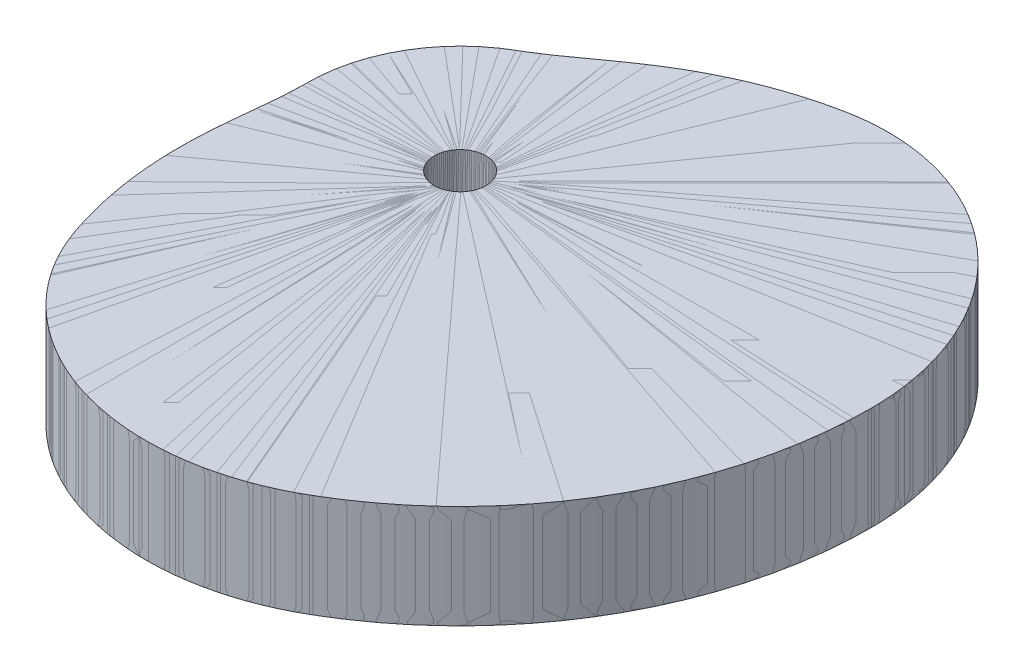
SolidWorks part; units mm, degrees
ref_plane "前视基准面" through (0, 0, 0) normal (0, 0, 1) x (1, 0, 0)
ref_plane "上视基准面" through (0, 0, 0) normal (0, 1, 0) x (1, 0, 0)
ref_plane "右视基准面" through (0, 0, 0) normal (1, 0, 0) x (0, 0, -1)
other "Configuration Table"
sketch "草图1" plane through (0, 0, 0) normal (0, 0, 1) x (1, 0, 0)
  line L0 (0, -20200) -> (0, 200) construction
  line L1 (5, 0) -> (80, 0)
  line L2 (80, 0) -> (80, -20)
  line L3 (80, -20) -> (5, -20)
  line L4 (5, -20) -> (5, 0)
revolve "旋转1" add sketch "草图1" angle 360 about L0
sketch "草图2" plane through (0, 0, 0) normal (0, 1, 0) x (1, 0, 0)
  line L0 (0, 0) -> (80, 0) construction
  arc A0 (79.5, 0) -> (79.027, 6.889) centre (29.0158, -0.0054) ccw
  arc A1 (79.027, 6.889) -> (77.6192, 13.6356) centre (29.3188, 0.0363) ccw
  arc A2 (77.6192, 13.6356) -> (75.3065, 20.1004) centre (29.7814, 0.1687) ccw
  arc A3 (75.3065, 20.1004) -> (72.1392, 26.149) centre (30.4291, 0.4546) ccw
  arc A4 (72.1392, 26.149) -> (68.1863, 31.6554) centre (31.21, 0.9379) ccw
  arc A5 (68.1863, 31.6554) -> (63.5342, 36.5035) centre (32.0595, 1.6461) ccw
  arc A6 (63.5342, 36.5035) -> (58.286, 40.5905) centre (32.9058, 2.5861) ccw
  arc A7 (58.286, 40.5905) -> (52.559, 43.8282) centre (33.6758, 3.7418) ccw
  arc A8 (52.559, 43.8282) -> (46.4828, 46.1451) centre (34.3014, 5.073) ccw
  arc A9 (46.4828, 46.1451) -> (40.1976, 47.4881) centre (34.7286, 6.5165) ccw
  arc A10 (40.1976, 47.4881) -> (33.8508, 47.8241) centre (34.9248, 7.9896) ccw
  arc A11 (33.8508, 47.8241) -> (27.59, 47.1393) centre (34.8892, 9.3651) ccw
  arc A12 (27.59, 47.1393) -> (21.6911, 45.7463) centre (41.7163, -25.8693) ccw
  arc A13 (21.6911, 45.7463) -> (16.3696, 44.035) centre (41.2849, -24.3103) ccw
  arc A14 (16.3696, 44.035) -> (11.6082, 42.1045) centre (41.16, -23.9463) ccw
  arc A15 (11.6082, 42.1045) -> (7.3715, 40.0439) centre (41.8148, -25.3862) ccw
  arc A16 (7.3715, 40.0439) -> (3.6125, 37.9311) centre (44.1291, -29.7547) ccw
  arc A17 (3.6125, 37.9311) -> (0.2748, 35.8322) centre (50.161, -39.7958) ccw
  arc A18 (0.2748, 35.8322) -> (-2.7058, 33.8002) centre (66.4018, -64.3674) ccw
  arc A19 (-2.7058, 33.8002) -> (-5.3989, 31.8746) centre (130.8056, -155.763) ccw
  arc A20 (-5.3989, 31.8746) -> (-7.8774, 30.0809) centre (-573.3815, 814.0785) cw
  arc A21 (-7.8774, 30.0809) -> (-10.2149, 28.4313) centre (-88.8574, 142.3512) cw
  arc A22 (-10.2149, 28.4313) -> (-12.4833, 26.9248) centre (-53.86, 91.691) cw
  arc A23 (-12.4833, 26.9248) -> (-14.75, 25.5477) centre (-44.8377, 77.6266) cw
  arc A24 (-14.75, 25.5477) -> (-29.5, 0) centre (0, 0) ccw
  arc A25 (-29.5, 0) -> (-29.5592, -2.6515) centre (-89.6454, 0.0173) cw
  arc A26 (-29.5592, -2.6515) -> (-29.7297, -5.3693) centre (-106.3368, 0.7987) cw
  arc A27 (-29.7297, -5.3693) -> (-29.9895, -8.2184) centre (-167.7085, 5.7772) cw
  arc A28 (-29.9895, -8.2184) -> (-30.3036, -11.2617) centre (-991.7034, 89.5237) cw
  arc A29 (-30.3036, -11.2617) -> (-30.6248, -14.5568) centre (200.2976, -35.3995) ccw
  arc A30 (-30.6248, -14.5568) -> (-30.8942, -18.1541) centre (88.9447, -25.3219) ccw
  arc A31 (-30.8942, -18.1541) -> (-31.0431, -22.0941) centre (59.5447, -23.5428) ccw
  arc A32 (-31.0431, -22.0941) -> (-30.9933, -26.4058) centre (47.8328, -23.3396) ccw
  arc A33 (-30.9933, -26.4058) -> (-30.6595, -31.1053) centre (42.8925, -23.5195) ccw
  arc A34 (-30.6595, -31.1053) -> (-29.9506, -36.194) centre (41.3181, -23.6724) ccw
  arc A35 (-29.9506, -36.194) -> (-28.772, -41.6582) centre (41.6958, -23.5986) ccw
  arc A36 (-28.772, -41.6582) -> (-27.0288, -47.4633) centre (43.2617, -23.1927) ccw
  arc A37 (-27.0288, -47.4633) -> (-24.4914, -53.2277) centre (9.3342, -34.8975) ccw
  arc A38 (-24.4914, -53.2277) -> (-21.0271, -58.5562) centre (10.5432, -34.2405) ccw
  arc A39 (-21.0271, -58.5562) -> (-16.7214, -63.3279) centre (11.7208, -33.3341) ccw
  arc A40 (-16.7214, -63.3279) -> (-11.6768, -67.4315) centre (12.7573, -32.2424) ccw
  arc A41 (-11.6768, -67.4315) -> (-6.0094, -70.7724) centre (13.5974, -31.035) ccw
  arc A42 (-6.0094, -70.7724) -> (0.1541, -73.274) centre (14.2133, -29.7903) ccw
  arc A43 (0.1541, -73.274) -> (6.6788, -74.8787) centre (14.6042, -28.5873) ccw
  arc A44 (6.6788, -74.8787) -> (13.4239, -75.5489) centre (14.7927, -27.4976) ccw
  arc A45 (13.4239, -75.5489) -> (20.2458, -75.2676) centre (14.8209, -26.5797) ccw
  arc A46 (20.2458, -75.2676) -> (27.0008, -74.038) centre (14.7446, -25.8758) ccw
  arc A47 (27.0008, -74.038) -> (33.5475, -71.8839) centre (14.6279, -25.409) ccw
  arc A48 (33.5475, -71.8839) -> (39.75, -68.849) centre (14.5126, -25.1257) ccw
  arc A49 (39.75, -68.849) -> (79.5, 0) centre (0, 0) ccw
extrude "切除-拉伸1" cut sketch "草图2" along normal blind 10 and the other way blind 30 flip side to cut
sketch "草图3" plane through (0, 0, 0) normal (0, 1, 0) x (1, 0, 0)
  circle A0 centre (0, 0) radius 5 construction
  circle A1 centre (0, 0) radius 5
  arc A50 (33.5475, -71.8839) -> (39.75, -68.849) centre (14.5126, -25.1257) ccw
  arc A51 (39.75, -68.849) -> (79.5, 0) centre (0, 0) ccw
  arc A52 (79.5, 0) -> (79.027, 6.889) centre (29.0158, -0.0054) ccw
  arc A53 (79.027, 6.889) -> (77.6192, 13.6356) centre (29.3188, 0.0363) ccw
  arc A54 (77.6192, 13.6356) -> (75.3065, 20.1004) centre (29.7814, 0.1687) ccw
  arc A55 (75.3065, 20.1004) -> (72.1392, 26.149) centre (30.4291, 0.4546) ccw
  arc A56 (72.1392, 26.149) -> (68.1863, 31.6554) centre (31.21, 0.9379) ccw
  arc A57 (68.1863, 31.6554) -> (63.5342, 36.5035) centre (32.0595, 1.6461) ccw
  arc A58 (63.5342, 36.5035) -> (58.286, 40.5905) centre (32.9058, 2.5861) ccw
  arc A59 (58.286, 40.5905) -> (52.559, 43.8282) centre (33.6758, 3.7418) ccw
  arc A60 (52.559, 43.8282) -> (46.4828, 46.1451) centre (34.3014, 5.073) ccw
  arc A61 (46.4828, 46.1451) -> (40.1976, 47.4881) centre (34.7286, 6.5165) ccw
  arc A62 (40.1976, 47.4881) -> (33.8508, 47.8241) centre (34.9248, 7.9896) ccw
  arc A63 (33.8508, 47.8241) -> (27.59, 47.1393) centre (34.8892, 9.3651) ccw
  arc A64 (27.59, 47.1393) -> (21.6911, 45.7463) centre (41.7163, -25.8693) ccw
  arc A65 (21.6911, 45.7463) -> (16.3696, 44.035) centre (41.2849, -24.3103) ccw
  arc A66 (16.3696, 44.035) -> (11.6082, 42.1045) centre (41.16, -23.9463) ccw
  arc A67 (11.6082, 42.1045) -> (7.3715, 40.0439) centre (41.8148, -25.3862) ccw
  arc A68 (7.3715, 40.0439) -> (3.6125, 37.9311) centre (44.1291, -29.7547) ccw
  arc A69 (3.6125, 37.9311) -> (0.2748, 35.8322) centre (50.161, -39.7958) ccw
  arc A70 (0.2748, 35.8322) -> (-2.7058, 33.8002) centre (66.4018, -64.3674) ccw
  arc A71 (-2.7058, 33.8002) -> (-5.3989, 31.8746) centre (130.8056, -155.763) ccw
  arc A72 (-7.8774, 30.0809) -> (-5.3989, 31.8746) centre (-573.3815, 814.0785) ccw
  arc A73 (-10.2149, 28.4313) -> (-7.8774, 30.0809) centre (-88.8574, 142.3512) ccw
  arc A74 (-12.4833, 26.9248) -> (-10.2149, 28.4313) centre (-53.86, 91.691) ccw
  arc A75 (-14.75, 25.5477) -> (-12.4833, 26.9248) centre (-44.8377, 77.6266) ccw
  arc A76 (-14.75, 25.5477) -> (-29.5, 0) centre (0, 0) ccw
  arc A77 (-29.5592, -2.6515) -> (-29.5, 0) centre (-89.6454, 0.0173) ccw
  arc A78 (-29.7297, -5.3693) -> (-29.5592, -2.6515) centre (-106.3368, 0.7987) ccw
  arc A79 (-29.9895, -8.2184) -> (-29.7297, -5.3693) centre (-167.7085, 5.7772) ccw
  arc A80 (-30.3036, -11.2617) -> (-29.9895, -8.2184) centre (-991.7034, 89.5237) ccw
  arc A81 (-30.3036, -11.2617) -> (-30.6248, -14.5568) centre (200.2976, -35.3995) ccw
  arc A82 (-30.6248, -14.5568) -> (-30.8942, -18.1541) centre (88.9447, -25.3219) ccw
  arc A83 (-30.8942, -18.1541) -> (-31.0431, -22.0941) centre (59.5447, -23.5428) ccw
  arc A84 (-31.0431, -22.0941) -> (-30.9933, -26.4058) centre (47.8328, -23.3396) ccw
  arc A85 (-30.9933, -26.4058) -> (-30.6595, -31.1053) centre (42.8925, -23.5195) ccw
  arc A86 (-30.6595, -31.1053) -> (-29.9506, -36.194) centre (41.3181, -23.6724) ccw
  arc A87 (-29.9506, -36.194) -> (-28.772, -41.6582) centre (41.6958, -23.5986) ccw
  arc A88 (-28.772, -41.6582) -> (-27.0288, -47.4633) centre (43.2617, -23.1927) ccw
  arc A89 (-27.0288, -47.4633) -> (-24.4914, -53.2277) centre (9.3342, -34.8975) ccw
  arc A90 (-24.4914, -53.2277) -> (-21.0271, -58.5562) centre (10.5432, -34.2405) ccw
  arc A91 (-21.0271, -58.5562) -> (-16.7214, -63.3279) centre (11.7208, -33.3341) ccw
  arc A92 (-16.7214, -63.3279) -> (-11.6768, -67.4315) centre (12.7573, -32.2424) ccw
  arc A93 (-11.6768, -67.4315) -> (-6.0094, -70.7724) centre (13.5974, -31.035) ccw
  arc A94 (-6.0094, -70.7724) -> (0.1541, -73.274) centre (14.2133, -29.7903) ccw
  arc A95 (0.1541, -73.274) -> (6.6788, -74.8787) centre (14.6042, -28.5873) ccw
  arc A96 (6.6788, -74.8787) -> (13.4239, -75.5489) centre (14.7927, -27.4976) ccw
  arc A97 (13.4239, -75.5489) -> (20.2458, -75.2676) centre (14.8209, -26.5797) ccw
  arc A98 (20.2458, -75.2676) -> (27.0008, -74.038) centre (14.7446, -25.8758) ccw
  arc A99 (27.0008, -74.038) -> (33.5475, -71.8839) centre (14.6279, -25.409) ccw
  arc A100 (33.5475, -71.8839) -> (39.75, -68.849) centre (14.5126, -25.1257) ccw construction
  arc A101 (39.75, -68.849) -> (79.5, 0) centre (0, 0) ccw construction
  arc A102 (79.5, 0) -> (79.027, 6.889) centre (29.0158, -0.0054) ccw construction
  arc A103 (79.027, 6.889) -> (77.6192, 13.6356) centre (29.3188, 0.0363) ccw construction
  arc A104 (77.6192, 13.6356) -> (75.3065, 20.1004) centre (29.7814, 0.1687) ccw construction
  arc A105 (75.3065, 20.1004) -> (72.1392, 26.149) centre (30.4291, 0.4546) ccw construction
  arc A106 (72.1392, 26.149) -> (68.1863, 31.6554) centre (31.21, 0.9379) ccw construction
  arc A107 (68.1863, 31.6554) -> (63.5342, 36.5035) centre (32.0595, 1.6461) ccw construction
  arc A108 (63.5342, 36.5035) -> (58.286, 40.5905) centre (32.9058, 2.5861) ccw construction
  arc A109 (58.286, 40.5905) -> (52.559, 43.8282) centre (33.6758, 3.7418) ccw construction
  arc A110 (52.559, 43.8282) -> (46.4828, 46.1451) centre (34.3014, 5.073) ccw construction
  arc A111 (46.4828, 46.1451) -> (40.1976, 47.4881) centre (34.7286, 6.5165) ccw construction
  arc A112 (40.1976, 47.4881) -> (33.8508, 47.8241) centre (34.9248, 7.9896) ccw construction
  arc A113 (33.8508, 47.8241) -> (27.59, 47.1393) centre (34.8892, 9.3651) ccw construction
  arc A114 (27.59, 47.1393) -> (21.6911, 45.7463) centre (41.7163, -25.8693) ccw construction
  arc A115 (21.6911, 45.7463) -> (16.3696, 44.035) centre (41.2849, -24.3103) ccw construction
  arc A116 (16.3696, 44.035) -> (11.6082, 42.1045) centre (41.16, -23.9463) ccw construction
  arc A117 (11.6082, 42.1045) -> (7.3715, 40.0439) centre (41.8148, -25.3862) ccw construction
  arc A118 (7.3715, 40.0439) -> (3.6125, 37.9311) centre (44.1291, -29.7547) ccw construction
  arc A119 (3.6125, 37.9311) -> (0.2748, 35.8322) centre (50.161, -39.7958) ccw construction
  arc A120 (0.2748, 35.8322) -> (-2.7058, 33.8002) centre (66.4018, -64.3674) ccw construction
  arc A121 (-2.7058, 33.8002) -> (-5.3989, 31.8746) centre (130.8056, -155.763) ccw construction
  arc A122 (-7.8774, 30.0809) -> (-5.3989, 31.8746) centre (-573.3815, 814.0785) ccw construction
  arc A123 (-10.2149, 28.4313) -> (-7.8774, 30.0809) centre (-88.8574, 142.3512) ccw construction
  arc A124 (-12.4833, 26.9248) -> (-10.2149, 28.4313) centre (-53.86, 91.691) ccw construction
  arc A125 (-14.75, 25.5477) -> (-12.4833, 26.9248) centre (-44.8377, 77.6266) ccw construction
  arc A126 (-14.75, 25.5477) -> (-29.5, 0) centre (0, 0) ccw construction
  arc A127 (-29.5592, -2.6515) -> (-29.5, 0) centre (-89.6454, 0.0173) ccw construction
  arc A128 (-29.7297, -5.3693) -> (-29.5592, -2.6515) centre (-106.3368, 0.7987) ccw construction
  arc A129 (-29.9895, -8.2184) -> (-29.7297, -5.3693) centre (-167.7085, 5.7772) ccw construction
  arc A130 (-30.3036, -11.2617) -> (-29.9895, -8.2184) centre (-991.7034, 89.5237) ccw construction
  arc A131 (-30.3036, -11.2617) -> (-30.6248, -14.5568) centre (200.2976, -35.3995) ccw construction
  arc A132 (-30.6248, -14.5568) -> (-30.8942, -18.1541) centre (88.9447, -25.3219) ccw construction
  arc A133 (-30.8942, -18.1541) -> (-31.0431, -22.0941) centre (59.5447, -23.5428) ccw construction
  arc A134 (-31.0431, -22.0941) -> (-30.9933, -26.4058) centre (47.8328, -23.3396) ccw construction
  arc A135 (-30.9933, -26.4058) -> (-30.6595, -31.1053) centre (42.8925, -23.5195) ccw construction
  arc A136 (-30.6595, -31.1053) -> (-29.9506, -36.194) centre (41.3181, -23.6724) ccw construction
  arc A137 (-29.9506, -36.194) -> (-28.772, -41.6582) centre (41.6958, -23.5986) ccw construction
  arc A138 (-28.772, -41.6582) -> (-27.0288, -47.4633) centre (43.2617, -23.1927) ccw construction
  arc A139 (-27.0288, -47.4633) -> (-24.4914, -53.2277) centre (9.3342, -34.8975) ccw construction
  arc A140 (-24.4914, -53.2277) -> (-21.0271, -58.5562) centre (10.5432, -34.2405) ccw construction
  arc A141 (-21.0271, -58.5562) -> (-16.7214, -63.3279) centre (11.7208, -33.3341) ccw construction
  arc A142 (-16.7214, -63.3279) -> (-11.6768, -67.4315) centre (12.7573, -32.2424) ccw construction
  arc A143 (-11.6768, -67.4315) -> (-6.0094, -70.7724) centre (13.5974, -31.035) ccw construction
  arc A144 (-6.0094, -70.7724) -> (0.1541, -73.274) centre (14.2133, -29.7903) ccw construction
  arc A145 (0.1541, -73.274) -> (6.6788, -74.8787) centre (14.6042, -28.5873) ccw construction
  arc A146 (6.6788, -74.8787) -> (13.4239, -75.5489) centre (14.7927, -27.4976) ccw construction
  arc A147 (13.4239, -75.5489) -> (20.2458, -75.2676) centre (14.8209, -26.5797) ccw construction
  arc A148 (20.2458, -75.2676) -> (27.0008, -74.038) centre (14.7446, -25.8758) ccw construction
  arc A149 (27.0008, -74.038) -> (33.5475, -71.8839) centre (14.6279, -25.409) ccw construction
  spline S0 degree 3 poles (15.132, -75.5679) (16.2711, -75.5606) (17.4092, -75.5137) (18.5451, -75.4271) (18.7027, -75.4151) (19.0178, -75.3895) (19.4901, -75.3467) (19.8047, -75.315) (19.9619, -75.2984) (20.1833, -75.275) (20.6257, -75.2253) (21.2884, -75.1418) (21.7293, -75.0802) (21.9495, -75.0479) (23.0829, -74.8819) (24.2098, -74.6767) (25.329, -74.4328) (25.4687, -74.4023) (25.7479, -74.3402) (26.1659, -74.2434) (26.4439, -74.1765) (26.5828, -74.1424) (26.8153, -74.0854) (27.2796, -73.968) (27.9736, -73.7818) (28.4344, -73.6511) (28.6643, -73.5842) (29.7682, -73.2625) (30.8604, -72.9032) (31.9396, -72.5065) (32.2995, -72.3742) (33.0163, -72.1013) (34.0825, -71.6672) (34.7861, -71.3619) (35.1362, -71.2052) (36.1876, -70.7346) (37.2224, -70.2283) (38.2392, -69.6869) (38.4087, -69.5967) (38.7465, -69.4143) (39.2506, -69.1357) (39.5838, -68.945) (39.75, -68.849) (39.9167, -68.7528) (40.2494, -68.5591) (40.7464, -68.2649) (41.0763, -68.0663) (41.2408, -67.9665) (64.9876, -53.5574) (78.8759, -29.5022) (79.4811, -1.7324) (79.4853, -1.5399) (79.4923, -1.155) (79.4986, -0.5775) (79.5, -0.1925) (79.5, 0) (79.5, 0.192) (79.4986, 0.5759) (79.4878, 1.1517) (79.4768, 1.5355) (79.4703, 1.7273) (79.4307, 2.8786) (79.3518, 4.0279) (79.2336, 5.1738) (79.1943, 5.5553) (79.1069, 6.3173) (78.9497, 7.4577) (78.8276, 8.2149) (78.7622, 8.5928) (78.5662, 9.7257) (78.3313, 10.8513) (78.0579, 11.9681) (78.001, 12.2007) (77.8837, 12.665) (77.6979, 13.3591) (77.5675, 13.8199) (77.5006, 14.0498) (77.4607, 14.1872) (77.3796, 14.4614) (77.2545, 14.8718) (77.1687, 15.1446) (77.1252, 15.2808) (76.7769, 16.3721) (76.391, 17.4506) (75.9682, 18.5151) (75.886, 18.722) (75.7189, 19.1346) (75.4599, 19.7503) (75.2817, 20.1583) (75.1913, 20.3617) (75.127, 20.5061) (74.9972, 20.7944) (74.7982, 21.2249) (74.6627, 21.5105) (74.5943, 21.6531) (74.1014, 22.68) (73.573, 23.6891) (73.0097, 24.6792) (72.9042, 24.8646) (72.6909, 25.234) (72.3635, 25.784) (72.1406, 26.1478) (72.0279, 26.3289) (71.9408, 26.4689) (71.7652, 26.7482) (71.4973, 27.1643) (71.3159, 27.4398) (71.2245, 27.5771) (70.5978, 28.5184) (69.9383, 29.4371) (69.2468, 30.332) (69.1203, 30.4956) (68.8653, 30.8212) (68.4765, 31.3047) (68.2132, 31.6236) (68.0805, 31.7822) (67.9724, 31.9114) (67.7549, 32.1687) (67.4243, 32.551) (67.2013, 32.8035) (67.0891, 32.9291) (66.3424, 33.7652) (65.5662, 34.5741) (64.7616, 35.3547) (64.617, 35.495) (64.3261, 35.7736) (63.8843, 36.186) (63.5863, 36.457) (63.4364, 36.5916) (63.3097, 36.7054) (63.055, 36.9315) (62.6691, 37.2664) (62.4093, 37.4868) (62.2789, 37.5963) (61.4286, 38.3097) (60.5529, 38.9916) (59.653, 39.6412) (59.4937, 39.7562) (59.1736, 39.9841) (58.6889, 40.3199) (58.363, 40.5395) (58.1994, 40.6482) (58.0567, 40.7431) (57.7702, 40.9311) (57.3371, 41.2081) (57.0463, 41.3894) (56.9003, 41.4792) (55.9655, 42.0545) (55.0099, 42.5948) (54.0349, 43.0991) (53.8646, 43.1872) (53.523, 43.3611) (53.0071, 43.6154) (52.6611, 43.7804) (52.4876, 43.8617) (52.3318, 43.9348) (52.0194, 44.079) (51.5481, 44.2896) (51.2323, 44.4262) (51.074, 44.4936) (50.0755, 44.9184) (49.0616, 45.305) (48.0338, 45.6528) (47.8569, 45.7127) (47.5025, 45.8301) (46.9684, 45.9992) (46.611, 46.1073) (46.432, 46.1601) (46.2662, 46.209) (45.9342, 46.3049) (45.4342, 46.4422) (45.0998, 46.5297) (44.9323, 46.5723) (43.893, 46.8371) (42.8441, 47.0612) (41.7873, 47.2444) (41.6086, 47.2753) (41.2508, 47.3349) (40.7129, 47.4173) (40.3536, 47.4674) (40.1739, 47.4913) (40.0013, 47.5142) (39.6559, 47.5579) (39.1369, 47.6164) (38.7905, 47.651) (38.6172, 47.6671) (37.5611, 47.7654) (36.5019, 47.8214) (35.4413, 47.8352) (35.2646, 47.8375) (34.9111, 47.8397) (34.3809, 47.836) (34.0275, 47.8288) (33.8508, 47.8241) (33.6758, 47.8193) (33.3257, 47.8076) (32.8008, 47.7826) (32.4511, 47.7611) (32.2764, 47.7493) (31.2277, 47.6779) (30.1828, 47.5636) (29.1434, 47.4066) (28.9702, 47.3804) (28.6242, 47.3258) (28.1061, 47.2379) (27.762, 47.1726) (27.59, 47.1393) (27.4247, 47.1073) (27.0942, 47.0422) (26.5991, 46.9412) (26.2696, 46.8716) (26.1049, 46.8362) (25.1169, 46.6241) (24.1334, 46.3919) (23.1548, 46.1396) (22.9918, 46.0976) (22.6659, 46.0124) (22.1779, 45.8813) (21.8533, 45.7917) (21.6911, 45.7463) (21.5415, 45.7045) (21.2426, 45.6199) (20.7951, 45.4901) (20.4973, 45.4016) (20.3486, 45.3569) (19.4561, 45.0887) (18.5689, 44.8034) (17.6874, 44.5011) (17.5405, 44.4507) (17.247, 44.349) (16.8077, 44.1936) (16.5155, 44.0882) (16.3696, 44.035) (16.2355, 43.9861) (15.9675, 43.8875) (15.5665, 43.7372) (15.2998, 43.6354) (15.1666, 43.5842) (14.3672, 43.2765) (13.5735, 42.9547) (12.7855, 42.6188) (12.6542, 42.5628) (12.3919, 42.4501) (11.9994, 42.2787) (11.7385, 42.1629) (11.6082, 42.1045) (11.4888, 42.0511) (11.2501, 41.9435) (10.893, 41.7802) (10.6555, 41.6701) (10.5369, 41.6148) (9.8252, 41.2825) (9.1189, 40.939) (8.4182, 40.5843) (8.3014, 40.5252) (8.0682, 40.4063) (7.7192, 40.2263) (7.4873, 40.1049) (7.3715, 40.0439) (7.2655, 39.9881) (7.0538, 39.8759) (6.7369, 39.7063) (6.5262, 39.5923) (6.421, 39.535) (5.7896, 39.1914) (5.163, 38.8392) (4.5413, 38.4785) (4.4377, 38.4184) (4.2307, 38.2977) (3.9211, 38.1153) (3.7153, 37.9927) (3.6125, 37.9311) (3.5185, 37.8748) (3.3308, 37.7619) (3.0498, 37.5916) (2.8629, 37.4773) (2.7695, 37.42) (2.2094, 37.0763) (1.6531, 36.7264) (1.1006, 36.3705) (1.0085, 36.3112) (0.8245, 36.1923) (0.5492, 36.013) (0.3662, 35.8926) (0.2748, 35.8322) (0.1911, 35.777) (0.024, 35.6664) (-0.2263, 35.4999) (-0.3929, 35.3885) (-0.4761, 35.3326) (-0.9754, 34.9977) (-1.4722, 34.659) (-1.9664, 34.3166) (-2.0488, 34.2596) (-2.2134, 34.1452) (-2.46, 33.9732) (-2.6239, 33.8579) (-2.7058, 33.8002) (-2.781, 33.7473) (-2.9313, 33.6413) (-3.1566, 33.482) (-3.3067, 33.3757) (-3.3817, 33.3224) (-3.8317, 33.0031) (-4.2805, 32.6821) (-4.7282, 32.3596) (-4.8718, 32.2562) (-5.1587, 32.049) (-5.5883, 31.7371) (-5.8747, 31.5293) (-6.018, 31.4254) (-6.4308, 31.1261) (-6.8439, 30.8272) (-7.2572, 30.5286) (-7.3261, 30.4788) (-7.4639, 30.3793) (-7.6706, 30.23) (-7.8085, 30.1306) (-7.8774, 30.0809) (-7.9418, 30.0344) (-8.0708, 29.9414) (-8.2646, 29.8025) (-8.3939, 29.7101) (-8.4586, 29.6639) (-8.8467, 29.387) (-9.2363, 29.1121) (-9.6273, 28.8391) (-9.6925, 28.7936) (-9.8229, 28.7028) (-10.0188, 28.5668) (-10.1495, 28.4764) (-10.2149, 28.4313) (-10.2772, 28.3883) (-10.4017, 28.3025) (-10.5892, 28.1745) (-10.7143, 28.0895) (-10.777, 28.0471) (-11.1528, 27.7927) (-11.5309, 27.5416) (-11.9112, 27.2939) (-11.9746, 27.2526) (-12.1015, 27.1702) (-12.2922, 27.0472) (-12.4196, 26.9656) (-12.4833, 26.9248) (-12.5454, 26.8852) (-12.6697, 26.806) (-12.8568, 26.6883) (-12.9817, 26.6102) (-13.0443, 26.5712) (-13.4195, 26.3375) (-13.7973, 26.108) (-14.1777, 25.8826) (-14.3046, 25.8074) (-14.5591, 25.6579) (-14.9427, 25.4368) (-15.196, 25.2854) (-15.3221, 25.2088) (-24.1155, 19.8641) (-29.2606, 10.9525) (-29.4925, 0.6649) (-29.4958, 0.5174) (-29.5003, 0.2223) (-29.4999, -0.2204) (-29.5022, -0.5155) (-29.5038, -0.6631) (-29.5088, -1.1051) (-29.5187, -1.5471) (-29.5335, -1.9889) (-29.5359, -2.0626) (-29.5411, -2.2098) (-29.5495, -2.4307) (-29.5559, -2.5779) (-29.5592, -2.6515) (-29.5626, -2.7271) (-29.5696, -2.8782) (-29.5808, -3.1049) (-29.5887, -3.256) (-29.5928, -3.3315) (-29.6172, -3.7847) (-29.6456, -4.2377) (-29.678, -4.6904) (-29.6834, -4.7659) (-29.6945, -4.9168) (-29.7115, -5.1431) (-29.7236, -5.2939) (-29.7297, -5.3693) (-29.7361, -5.4485) (-29.749, -5.6069) (-29.7688, -5.8445) (-29.7823, -6.0029) (-29.7891, -6.0821) (-29.8299, -6.5571) (-29.8732, -7.032) (-29.919, -7.5066) (-29.9266, -7.5858) (-29.942, -7.7439) (-29.9654, -7.9812) (-29.9814, -8.1394) (-29.9895, -8.2184) (-29.9981, -8.303) (-30.0153, -8.4721) (-30.0412, -8.7257) (-30.0585, -8.8948) (-30.0671, -8.9793) (-30.1191, -9.4866) (-30.1714, -9.9938) (-30.2242, -10.501) (-30.2425, -10.677) (-30.2792, -11.0289) (-30.3346, -11.5569) (-30.3705, -11.909) (-30.3883, -12.085) (-30.4438, -12.634) (-30.4974, -13.1832) (-30.5489, -13.7326) (-30.5575, -13.8242) (-30.5746, -14.0073) (-30.5999, -14.282) (-30.6165, -14.4652) (-30.6248, -14.5568) (-30.6338, -14.6566) (-30.6517, -14.8562) (-30.6773, -15.1557) (-30.6941, -15.3555) (-30.7023, -15.4553) (-30.7517, -16.0545) (-30.7966, -16.6541) (-30.837, -17.254) (-30.8438, -17.354) (-30.857, -17.554) (-30.876, -17.854) (-30.8883, -18.054) (-30.8942, -18.1541) (-30.9008, -18.2634) (-30.9136, -18.4821) (-30.9312, -18.8102) (-30.9422, -19.029) (-30.9475, -19.1384) (-30.9795, -19.7948) (-31.0043, -20.4515) (-31.0219, -21.1085) (-31.0249, -21.218) (-31.0304, -21.437) (-31.0374, -21.7655) (-31.0413, -21.9845) (-31.0431, -22.0941) (-31.045, -22.2138) (-31.0483, -22.4534) (-31.0514, -22.8128) (-31.0525, -23.0524) (-31.0527, -23.1722) (-31.0542, -23.8909) (-31.0459, -24.6097) (-31.0278, -25.3282) (-31.0248, -25.448) (-31.0182, -25.6875) (-31.0067, -26.0467) (-30.9979, -26.2861) (-30.9933, -26.4058) (-30.9882, -26.5366) (-30.9774, -26.7982) (-30.9588, -27.1904) (-30.9451, -27.4518) (-30.9379, -27.5825) (-30.8948, -28.3667) (-30.8391, -29.1501) (-30.771, -29.9326) (-30.7597, -30.063) (-30.7363, -30.3237) (-30.6991, -30.7146) (-30.6729, -30.9751) (-30.6595, -31.1053) (-30.6448, -31.2473) (-30.6147, -31.5312) (-30.5669, -31.9568) (-30.5334, -32.2403) (-30.5162, -32.382) (-30.4131, -33.2323) (-30.2949, -34.0806) (-30.1617, -34.9267) (-30.1395, -35.0677) (-30.0943, -35.3496) (-30.0239, -35.7721) (-29.9753, -36.0534) (-29.9506, -36.194) (-29.9237, -36.347) (-29.869, -36.6527) (-29.7839, -37.1108) (-29.7252, -37.4159) (-29.6954, -37.5683) (-29.5164, -38.4829) (-29.3199, -39.3938) (-29.106, -40.3009) (-29.0703, -40.452) (-28.998, -40.7541) (-28.8867, -41.2066) (-28.8105, -41.5077) (-28.772, -41.6582) (-28.7301, -41.8213) (-28.6454, -42.1473) (-28.515, -42.6354) (-28.4258, -42.9602) (-28.3807, -43.1225) (-28.1098, -44.0961) (-27.8192, -45.0639) (-27.5089, -46.0257) (-27.4572, -46.1859) (-27.3527, -46.5061) (-27.1927, -46.9854) (-27.0838, -47.3041) (-27.0288, -47.4633) (-26.9717, -47.6289) (-26.8562, -47.9595) (-26.6732, -48.4522) (-26.5476, -48.7792) (-26.4836, -48.9422) (-26.0999, -49.9208) (-25.6764, -50.8829) (-25.2139, -51.8268) (-25.1368, -51.9841) (-24.9805, -52.2976) (-24.7398, -52.7647) (-24.5749, -53.0737) (-24.4914, -53.2277) (-24.4072, -53.3831) (-24.2368, -53.6927) (-23.9748, -54.1538) (-23.7962, -54.4588) (-23.7058, -54.6106) (-23.1636, -55.5223) (-22.5855, -56.4115) (-21.9723, -57.277) (-21.8717, -57.4191) (-21.6686, -57.7018) (-21.3584, -58.122) (-21.1479, -58.3993) (-21.0418, -58.5372) (-20.9312, -58.681) (-20.7081, -58.967) (-20.3678, -59.3917) (-20.1373, -59.6718) (-20.0212, -59.8111) (-19.3342, -60.6347) (-18.6156, -61.431) (-17.8666, -62.1987) (-17.746, -62.3224) (-17.5031, -62.5683) (-17.1341, -62.9326) (-16.8851, -63.1722) (-16.7599, -63.2913) (-16.6245, -63.4199) (-16.3523, -63.6754) (-15.9388, -64.0534) (-15.6599, -64.3017) (-15.5196, -64.4249) (-14.7045, -65.1411) (-13.8627, -65.8259) (-12.9955, -66.4782) (-12.858, -66.5816) (-12.5818, -66.7868) (-12.1638, -67.0897) (-11.8827, -67.2881) (-11.7416, -67.3864) (-11.5843, -67.496) (-11.2684, -67.7132) (-10.7903, -68.0328) (-10.4689, -68.2417) (-10.3075, -68.3451) (-9.3832, -68.9373) (-8.4376, -69.4948) (-7.4719, -70.0167) (-7.3211, -70.0982) (-7.0187, -70.2594) (-6.5623, -70.496) (-6.2562, -70.6501) (-6.1027, -70.7262) (-5.9267, -70.8136) (-5.5736, -70.986) (-5.0405, -71.2379) (-4.683, -71.4011) (-4.5037, -71.4816) (-3.4912, -71.9362) (-2.4628, -72.3536) (-1.4199, -72.7332) (-1.2599, -72.7915) (-0.9392, -72.9062) (-0.4561, -73.073) (-0.1329, -73.1805) (0.029, -73.2333) (0.2205, -73.2959) (0.6042, -73.4184) (1.1822, -73.5948) (1.569, -73.7075) (1.7627, -73.7625) (2.841, -74.0691) (3.9296, -74.3368) (5.0271, -74.5654) (5.192, -74.5998) (5.5222, -74.6667) (6.0186, -74.7618) (6.3501, -74.8215) (6.5161, -74.8506) (6.7198, -74.8862) (7.1276, -74.9547) (7.7408, -75.0497) (8.1502, -75.1077) (8.3551, -75.1354) (9.4758, -75.2869) (10.6012, -75.3987) (11.7298, -75.4708) (11.8944, -75.4813) (12.2237, -75.5006) (12.718, -75.5245) (13.0476, -75.537) (13.2125, -75.5425) (13.4257, -75.5495) (13.8521, -75.5607) (14.4921, -75.5692) (14.9187, -75.5692) (15.132, -75.5679) (16.2711, -75.5606) (17.4092, -75.5137) knots -0.001752 0 0 0 0.009351 0.009351 0.009351 0.01065 0.011948 0.013246 0.013246 0.013246 0.015074 0.016902 0.01873 0.01873 0.01873 0.028134 0.028134 0.028134 0.029308 0.030482 0.031657 0.031657 0.031657 0.033623 0.03559 0.037556 0.037556 0.037556 0.046996 0.046996 0.046996 0.050145 0.053294 0.056444 0.056444 0.056444 0.065901 0.065901 0.065901 0.067477 0.069054 0.07063 0.07063 0.07063 0.072211 0.073792 0.075373 0.075373 0.075373 0.284742 0.284742 0.284742 0.286323 0.287904 0.289485 0.289485 0.289485 0.291061 0.292638 0.294214 0.294214 0.294214 0.303672 0.303672 0.303672 0.306821 0.30997 0.31312 0.31312 0.31312 0.322559 0.322559 0.322559 0.324525 0.326492 0.328458 0.328458 0.328458 0.329633 0.330807 0.331981 0.331981 0.331981 0.341385 0.341385 0.341385 0.343213 0.345041 0.346869 0.346869 0.346869 0.348167 0.349466 0.350764 0.350764 0.350764 0.360115 0.360115 0.360115 0.361867 0.363619 0.365371 0.365371 0.365371 0.366725 0.36808 0.369434 0.369434 0.369434 0.378718 0.378718 0.378718 0.380416 0.382114 0.383813 0.383813 0.383813 0.385196 0.386579 0.387963 0.387963 0.387963 0.397166 0.397166 0.397166 0.39882 0.400474 0.402128 0.402128 0.402128 0.403527 0.404925 0.406324 0.406324 0.406324 0.415435 0.415435 0.415435 0.417049 0.418662 0.420276 0.420276 0.420276 0.421683 0.42309 0.424497 0.424497 0.424497 0.433509 0.433509 0.433509 0.435083 0.436657 0.438231 0.438231 0.438231 0.439644 0.441057 0.44247 0.44247 0.44247 0.451377 0.451377 0.451377 0.45291 0.454443 0.455977 0.455977 0.455977 0.457396 0.458815 0.460234 0.460234 0.460234 0.469038 0.469038 0.469038 0.470528 0.472017 0.473507 0.473507 0.473507 0.474936 0.476366 0.477795 0.477795 0.477795 0.486501 0.486501 0.486501 0.487953 0.489404 0.490856 0.490856 0.490856 0.492294 0.493732 0.49517 0.49517 0.49517 0.503798 0.503798 0.503798 0.505237 0.506675 0.508113 0.508113 0.508113 0.509496 0.510879 0.512263 0.512263 0.512263 0.520561 0.520561 0.520561 0.521944 0.523327 0.52471 0.52471 0.52471 0.525986 0.527261 0.528537 0.528537 0.528537 0.536189 0.536189 0.536189 0.537465 0.53874 0.540016 0.540016 0.540016 0.541188 0.54236 0.543533 0.543533 0.543533 0.550566 0.550566 0.550566 0.551739 0.552911 0.554083 0.554083 0.554083 0.555158 0.556233 0.557308 0.557308 0.557308 0.563758 0.563758 0.563758 0.564833 0.565908 0.566983 0.566983 0.566983 0.567966 0.56895 0.569934 0.569934 0.569934 0.575837 0.575837 0.575837 0.576821 0.577804 0.578788 0.578788 0.578788 0.579688 0.580587 0.581487 0.581487 0.581487 0.586884 0.586884 0.586884 0.587784 0.588683 0.589583 0.589583 0.589583 0.590406 0.591229 0.592052 0.592052 0.592052 0.596989 0.596989 0.596989 0.597812 0.598635 0.599458 0.599458 0.599458 0.600214 0.600969 0.601724 0.601724 0.601724 0.606256 0.606256 0.606256 0.607709 0.609162 0.610615 0.610615 0.610615 0.614803 0.614803 0.614803 0.615501 0.616199 0.616897 0.616897 0.616897 0.61755 0.618202 0.618855 0.618855 0.618855 0.622771 0.622771 0.622771 0.623424 0.624076 0.624729 0.624729 0.624729 0.62535 0.625972 0.626593 0.626593 0.626593 0.63032 0.63032 0.63032 0.630941 0.631563 0.632184 0.632184 0.632184 0.632789 0.633394 0.633999 0.633999 0.633999 0.63763 0.63763 0.63763 0.638842 0.640054 0.641265 0.641265 0.641265 0.71885 0.71885 0.71885 0.720062 0.721274 0.722485 0.722485 0.722485 0.726116 0.726116 0.726116 0.726721 0.727326 0.727931 0.727931 0.727931 0.728552 0.729174 0.729795 0.729795 0.729795 0.733522 0.733522 0.733522 0.734144 0.734765 0.735386 0.735386 0.735386 0.736039 0.736691 0.737344 0.737344 0.737344 0.74126 0.74126 0.74126 0.741913 0.742566 0.743218 0.743218 0.743218 0.743916 0.744614 0.745312 0.745312 0.745312 0.7495 0.7495 0.7495 0.750953 0.752406 0.753859 0.753859 0.753859 0.758391 0.758391 0.758391 0.759146 0.759902 0.760657 0.760657 0.760657 0.76148 0.762303 0.763126 0.763126 0.763126 0.768064 0.768064 0.768064 0.768887 0.76971 0.770533 0.770533 0.770533 0.771432 0.772332 0.773231 0.773231 0.773231 0.778628 0.778628 0.778628 0.779528 0.780427 0.781327 0.781327 0.781327 0.782311 0.783295 0.784278 0.784278 0.784278 0.790181 0.790181 0.790181 0.791165 0.792149 0.793133 0.793133 0.793133 0.794208 0.795283 0.796358 0.796358 0.796358 0.802807 0.802807 0.802807 0.803882 0.804957 0.806032 0.806032 0.806032 0.807204 0.808377 0.809549 0.809549 0.809549 0.816583 0.816583 0.816583 0.817755 0.818927 0.820099 0.820099 0.820099 0.821375 0.82265 0.823926 0.823926 0.823926 0.831579 0.831579 0.831579 0.832854 0.83413 0.835405 0.835405 0.835405 0.836788 0.838171 0.839554 0.839554 0.839554 0.847853 0.847853 0.847853 0.849236 0.850619 0.852002 0.852002 0.852002 0.85344 0.854879 0.856317 0.856317 0.856317 0.864945 0.864945 0.864945 0.866383 0.867821 0.86926 0.86926 0.86926 0.870711 0.872162 0.873614 0.873614 0.873614 0.88232 0.88232 0.88232 0.88375 0.885179 0.886609 0.886609 0.886609 0.888098 0.889588 0.891077 0.891077 0.891077 0.899881 0.899881 0.899881 0.9013 0.902719 0.904139 0.904139 0.904139 0.905672 0.907205 0.908738 0.908738 0.908738 0.917646 0.917646 0.917646 0.919059 0.920471 0.921884 0.921884 0.921884 0.923458 0.925032 0.926607 0.926607 0.926607 0.935618 0.935618 0.935618 0.937025 0.938432 0.939839 0.939839 0.939839 0.941453 0.943067 0.94468 0.94468 0.94468 0.953791 0.953791 0.953791 0.95519 0.956589 0.957987 0.957987 0.957987 0.959641 0.961296 0.96295 0.96295 0.96295 0.972153 0.972153 0.972153 0.973536 0.974919 0.976303 0.976303 0.976303 0.978001 0.979699 0.981397 0.981397 0.981397 0.990681 0.990681 0.990681 0.992036 0.99339 0.994745 0.994745 0.994745 0.996496 0.998248 1 1 1 1.009351 1.009351 1.009351 weights 1 0.999595 0.999595 1 1 1 1 1 1 1 1 1 1 1 0.999602 0.999602 1 1 1 1 1 1 1 1 1 1 1 0.999606 0.999606 1 1 1 1 1 1 0.99961 0.99961 1 1 1 1 1 1 1 1 1 1 1 0.91781 0.91781 1 1 1 1 1 1 1 1 1 1 1 0.99961 0.99961 1 1 1 1 1 1 0.999606 0.999606 1 1 1 1 1 1 1 1 1 1 1 0.999602 0.999602 1 1 1 1 1 1 1 1 1 1 1 0.999595 0.999595 1 1 1 1 1 1 1 1 1 1 1 0.999585 0.999585 1 1 1 1 1 1 1 1 1 1 1 0.999573 0.999573 1 1 1 1 1 1 1 1 1 1 1 0.999558 0.999558 1 1 1 1 1 1 1 1 1 1 1 0.99954 0.99954 1 1 1 1 1 1 1 1 1 1 1 0.999519 0.999519 1 1 1 1 1 1 1 1 1 1 1 0.999495 0.999495 1 1 1 1 1 1 1 1 1 1 1 0.999469 0.999469 1 1 1 1 1 1 1 1 1 1 1 0.999441 0.999441 1 1 1 1 1 1 1 1 1 1 1 0.999862 0.999862 1 1 1 1 1 1 1 1 1 1 1 0.999877 0.999877 1 1 1 1 1 1 1 1 1 1 1 0.999895 0.999895 1 1 1 1 1 1 1 1 1 1 1 0.999915 0.999915 1 1 1 1 1 1 1 1 1 1 1 0.999938 0.999938 1 1 1 1 1 1 1 1 1 1 1 0.999961 0.999961 1 1 1 1 1 1 1 1 1 1 1 0.999981 0.999981 1 1 1 1 1 1 1 1 1 1 1 0.999996 0.999996 1 1 1 1 1 1 1 1 1 1 1 1 1 1 1 1 1 1 1 0.999991 0.999991 1 1 1 1 1 1 1 1 1 1 1 0.999974 0.999974 1 1 1 1 1 1 1 1 1 1 1 0.999959 0.999959 1 1 1 1 1 1 0.91805 0.91805 1 1 1 1 1 1 0.999959 0.999959 1 1 1 1 1 1 1 1 1 1 1 0.999974 0.999974 1 1 1 1 1 1 1 1 1 1 1 0.999991 0.999991 1 1 1 1 1 1 1 1 1 1 1 1 1 1 1 1 1 1 1 0.999996 0.999996 1 1 1 1 1 1 1 1 1 1 1 0.999981 0.999981 1 1 1 1 1 1 1 1 1 1 1 0.999961 0.999961 1 1 1 1 1 1 1 1 1 1 1 0.999938 0.999938 1 1 1 1 1 1 1 1 1 1 1 0.999915 0.999915 1 1 1 1 1 1 1 1 1 1 1 0.999895 0.999895 1 1 1 1 1 1 1 1 1 1 1 0.999877 0.999877 1 1 1 1 1 1 1 1 1 1 1 0.999862 0.999862 1 1 1 1 1 1 1 1 1 1 1 0.999441 0.999441 1 1 1 1 1 1 1 1 1 1 1 0.999469 0.999469 1 1 1 1 1 1 1 1 1 1 1 0.999495 0.999495 1 1 1 1 1 1 1 1 1 1 1 0.999519 0.999519 1 1 1 1 1 1 1 1 1 1 1 0.99954 0.99954 1 1 1 1 1 1 1 1 1 1 1 0.999558 0.999558 1 1 1 1 1 1 1 1 1 1 1 0.999573 0.999573 1 1 1 1 1 1 1 1 1 1 1 0.999585 0.999585 1 1 1 1 1 1 1 1 1 1 1 0.999595 0.999595 only from (15.132, -75.5679) to (15.132, -75.5679)
  dimension "D1" = 0
extrude "凸台-拉伸1" add sketch "草图3" against normal up to surface (20 mm away) separate body up to face at (0, -20, -5)
sketch "草图4" plane through (0, 0, 0) normal (0, 1, 0) x (1, 0, 0)
  circle A0 centre (0, 0) radius 5
sketch "草图5" plane through (0, -20, 0) normal (0, -1, 0) x (1, 0, 0)
  circle A0 centre (0, 0) radius 5
